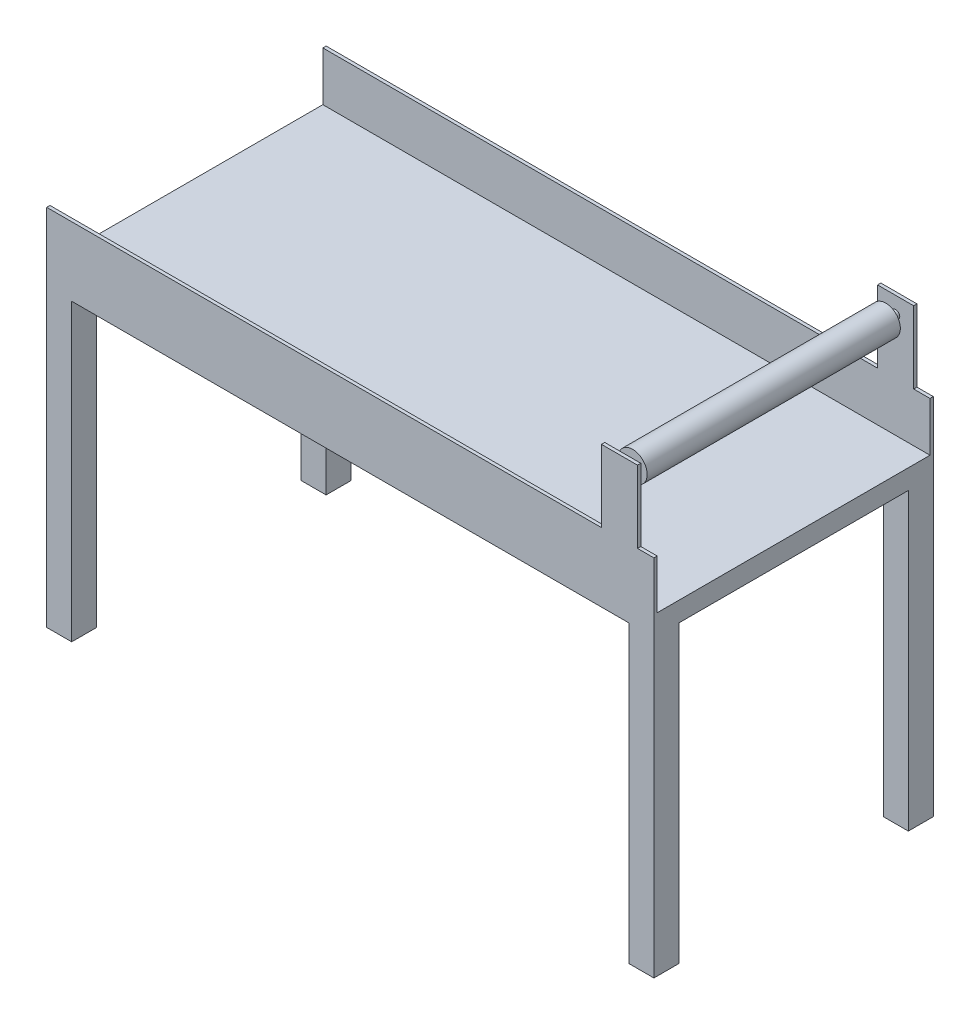
SolidWorks part; units mm, degrees
ref_plane "Alzado" through (0, 0, 0) normal (0, 0, 1) x (1, 0, 0)
ref_plane "Planta" through (0, 0, 0) normal (0, 1, 0) x (1, 0, 0)
ref_plane "Vista lateral" through (0, 0, 0) normal (1, 0, 0) x (0, 0, -1)
sketch "Croquis2" plane through (0, 0, 0) normal (0, 1, 0) x (1, 0, 0)
  line L0 (76.2, 0) -> (1776.2, 0) construction
  line L1 (0, 0) -> (76.2, 0)
  line L2 (0, 0) -> (0, -76.2)
  line L3 (0, -76.2) -> (76.2, -76.2)
  line L4 (76.2, 0) -> (76.2, -76.2)
  line L5 (0, -76.2) -> (0, -426.2) construction
  line L6 (0, -426.2) -> (926.2, -426.2) construction
  line L7 (1776.2, 0) -> (1852.4, 0)
  line L8 (1776.2, 0) -> (1776.2, -76.2)
  line L9 (1776.2, -76.2) -> (1852.4, -76.2)
  line L10 (1852.4, 0) -> (1852.4, -76.2)
  line L11 (926.2, -426.2) -> (926.2, 0) construction
  line L12 (76.2, -852.4) -> (1776.2, -852.4) construction
  line L13 (1852.4, -852.4) -> (1852.4, -776.2)
  line L14 (1776.2, -776.2) -> (1852.4, -776.2)
  line L15 (1776.2, -852.4) -> (1776.2, -776.2)
  line L16 (1776.2, -852.4) -> (1852.4, -852.4)
  line L17 (76.2, -852.4) -> (76.2, -776.2)
  line L18 (0, -776.2) -> (76.2, -776.2)
  line L19 (0, -852.4) -> (0, -776.2)
  line L20 (0, -852.4) -> (76.2, -852.4)
  dimension "D1" = 76.2
  dimension "D2" = 76.2
  dimension "D3" = 76.2
  dimension "D4" = 76.2
  dimension "D5" = 1700
  dimension "D8" = 350
extrude "Saliente-Extruir1" add sketch "Croquis2" along normal blind 900
sketch "Croquis3" plane through (0, 900, 0) normal (0, 1, 0) x (1, 0, 0)
  line L1 (0, 0) -> (1852.4, 0)
  line L2 (0, 0) -> (0, -852.4)
  line L3 (0, -852.4) -> (1852.4, -852.4)
  line L4 (1852.4, 0) -> (1852.4, -852.4)
extrude "Saliente-Extruir2" add sketch "Croquis3" along normal blind 210
sketch "Croquis4" plane through (0, 0, 0) normal (-1, 0, 0) x (0, 0, 1)
  line L0 (0, 1110) -> (852.4, 1110) construction
  line L1 (10, 1110) -> (842.4, 1110)
  line L2 (10, 1110) -> (10, 960)
  line L3 (10, 960) -> (842.4, 960)
  line L4 (842.4, 1110) -> (842.4, 960)
  line L5 (0, 1110) -> (0, 0) construction
  line L6 (852.4, 1110) -> (852.4, 0) construction
  dimension "D1" = 10
  dimension "D2" = 10
  dimension "D3" = 150
extrude "Cortar-Extruir1" cut sketch "Croquis4" against normal up to surface (1852.4 mm away) up to face at (1852.4, 502.5, 426.2)
sketch "Croquis5" plane through (0, 1110, 0) normal (0, 1, 0) x (1, 0, 0)
  line L0 (1852.4, 0) -> (0, 0) construction
  line L1 (1802.4, 0) -> (1692.4, 0)
  line L2 (1802.4, 0) -> (1802.4, -10)
  line L3 (1802.4, -10) -> (1692.4, -10)
  line L4 (1692.4, 0) -> (1692.4, -10)
  line L5 (1852.4, -10) -> (0, -10) construction
  line L6 (1852.4, -426.2) -> (1344.5554, -426.2) construction
  line L7 (1852.4, -842.4) -> (1852.4, -10) construction
  line L8 (1692.4, -852.4) -> (1692.4, -842.4)
  line L9 (1802.4, -842.4) -> (1692.4, -842.4)
  line L10 (1802.4, -852.4) -> (1802.4, -842.4)
  line L11 (1802.4, -852.4) -> (1692.4, -852.4)
  dimension "D1" = 50
  dimension "D2" = 110
extrude "Saliente-Extruir3" add sketch "Croquis5" along normal blind 220
sketch "Croquis6" plane through (0, 0, 852.4) normal (0, 0, 1) x (1, 0, 0)
  line L0 (1747.4, 1330) -> (1747.4, 1280) construction
  line L1 (1692.4, 1330) -> (1802.4, 1330) construction
  circle A0 centre (1747.4, 1280) radius 12.7
  dimension "D2" = 25.4
  dimension "D1" = 50
extrude "Saliente-Extruir4" add sketch "Croquis6" against normal blind 40
sketch "Croquis7" plane through (0, 0, 0) normal (0, 0, -1) x (-1, 0, 0)
  circle A0 centre (-1747.4, 1280) radius 12.7
extrude "Saliente-Extruir5" add sketch "Croquis7" against normal blind 40
sketch "Croquis8" plane through (0, 0, 40) normal (0, 0, 1) x (1, 0, 0)
  circle A0 centre (1747.4, 1280) radius 44.45
  dimension "D1" = 88.9
extrude "Saliente-Extruir6" add sketch "Croquis8" along normal up to surface (772.4 mm away) up to face at (1760.1, 1280, 812.4)
